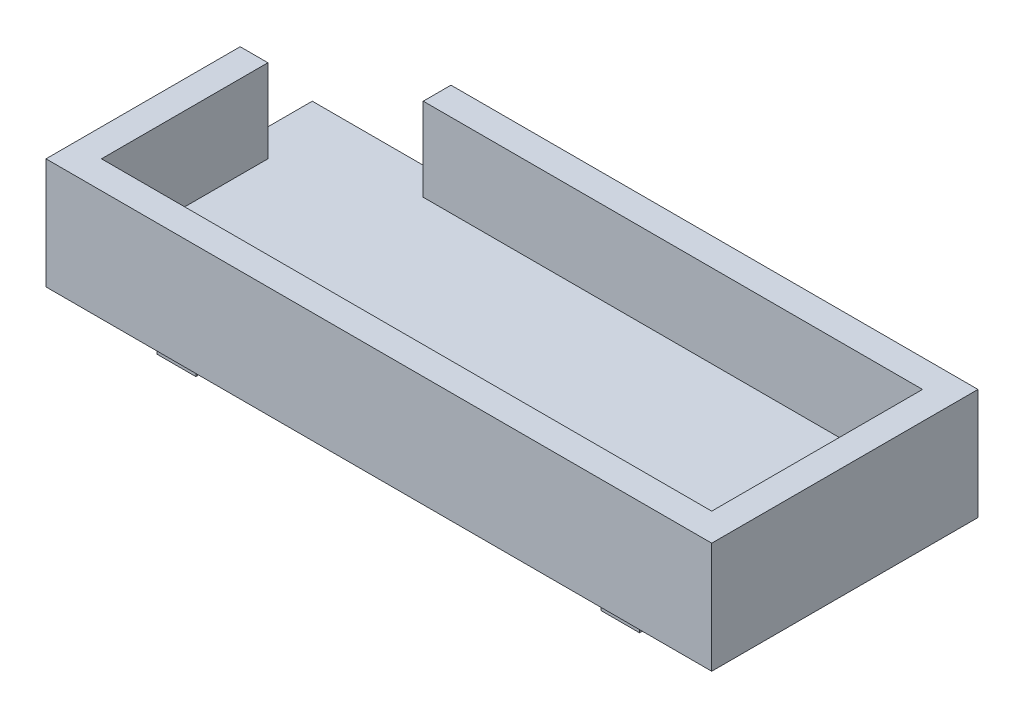
SolidWorks part; units mm, degrees
ref_plane "Front" through (0, 0, 0) normal (0, 0, 1) x (1, 0, 0)
ref_plane "Top" through (0, 0, 0) normal (0, 1, 0) x (1, 0, 0)
ref_plane "Right" through (0, 0, 0) normal (1, 0, 0) x (0, 0, -1)
sketch "Sketch1" plane through (0, 0, 0) normal (0, 1, 0) x (1, 0, 0)
  line L1 (0, 0) -> (120, 0)
  line L2 (0, 0) -> (0, 48)
  line L3 (0, 48) -> (120, 48)
  line L4 (120, 0) -> (120, 48)
  dimension "D1" = 120
  dimension "D2" = 48
extrude "Boss-Extrude1" add sketch "Sketch1" along normal blind 5 contours L3 L4 L1 L2
sketch "Sketch2" plane through (0, 5, 0) normal (0, 1, 0) x (1, 0, 0)
  line L0 (120, 48) -> (25, 48)
  line L1 (0, 48) -> (120, 48) construction
  line L2 (25, 48) -> (25, 43)
  line L3 (25, 43) -> (115, 43)
  line L4 (115, 43) -> (115, 5)
  line L5 (115, 5) -> (5, 5)
  line L6 (5, 5) -> (5, 35)
  line L7 (5, 35) -> (0, 35)
  line L8 (0, 0) -> (0, 48) construction
  line L9 (0, 35) -> (0, 0)
  line L10 (0, 0) -> (120, 0)
  line L11 (120, 0) -> (120, 48)
  dimension "D1" = 5
  dimension "D2" = 5
  dimension "D3" = 5
  dimension "D4" = 5
  dimension "D5" = 90
  dimension "D6" = 30
extrude "Boss-Extrude2" add sketch "Sketch2" along normal blind 15
sketch "Sketch3" plane through (0, 0, 0) normal (0, -1, 0) x (-1, 0, 0)
  line L0 (-103.5, 11.5) -> (-103.5, 15)
  line L1 (-103.5, 3.5) -> (-96.5, 3.5)
  line L2 (-103.5, 3.5) -> (-103.5, 7)
  line L3 (-103.5, 7) -> (-96.5, 7)
  line L4 (-96.5, 3.5) -> (-96.5, 7)
  line L5 (-120, 0) -> (-120, 48) construction
  line L6 (-103.5, 11.5) -> (-96.5, 11.5)
  line L7 (0, 0) -> (-120, 0) construction
  line L8 (-96.5, 11.5) -> (-96.5, 15)
  line L9 (-103.5, 15) -> (-96.5, 15)
  line L10 (-103.5, 19.5) -> (-103.5, 23)
  line L11 (-103.5, 19.5) -> (-96.5, 19.5)
  line L12 (-96.5, 19.5) -> (-96.5, 23)
  line L13 (-103.5, 23) -> (-96.5, 23)
  line L15 (0, 48) -> (-120, 48) construction
  line L16 (-60, 0) -> (-60, 48)
  line L17 (-16.5, 7) -> (-23.5, 7)
  line L18 (-23.5, 3.5) -> (-23.5, 7)
  line L19 (-16.5, 3.5) -> (-23.5, 3.5)
  line L20 (-16.5, 3.5) -> (-16.5, 7)
  line L21 (-16.5, 11.5) -> (-23.5, 11.5)
  line L22 (-23.5, 11.5) -> (-23.5, 15)
  line L23 (-16.5, 15) -> (-23.5, 15)
  line L24 (-16.5, 11.5) -> (-16.5, 15)
  line L25 (-16.5, 19.5) -> (-23.5, 19.5)
  line L26 (-23.5, 19.5) -> (-23.5, 23)
  line L27 (-16.5, 23) -> (-23.5, 23)
  line L28 (-16.5, 19.5) -> (-16.5, 23)
  dimension "D1" = 7
  dimension "D2" = 3.5
  dimension "D3" = 16.5
  dimension "D4" = 3.5
  dimension "D6" = 8
  dimension "D5" = 3
extrude "Boss-Extrude3" add sketch "Sketch3" along normal blind 4 contours L13 L10 L11 L12 | L9 L0 L6 L8 | L1 L4 L3 L2 | L25 L28 L27 L26 | L21 L24 L23 L22 | L19 L20 L17 L18
